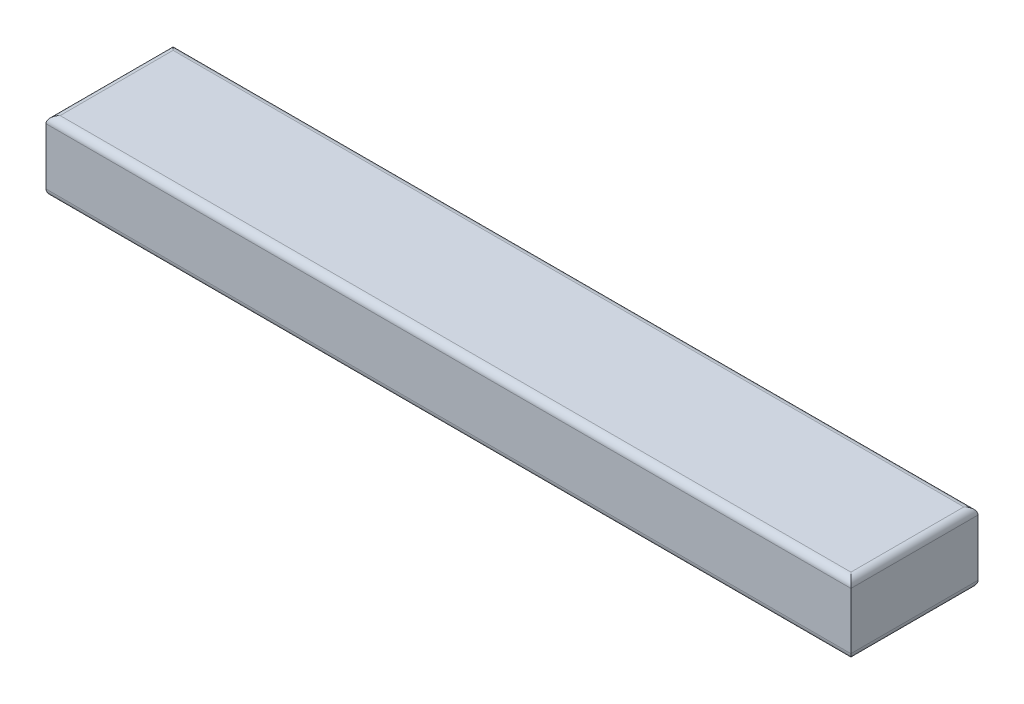
SolidWorks part; units mm, degrees
material "NEOPRENE"
ref_plane "Front Plane" through (0, 0, 0) normal (0, 0, 1) x (1, 0, 0)
ref_plane "Top Plane" through (0, 0, 0) normal (0, 1, 0) x (1, 0, 0)
ref_plane "Right Plane" through (0, 0, 0) normal (1, 0, 0) x (0, 0, -1)
sketch "Sketch2" plane through (0, 0, 0) normal (0, 1, 0) x (1, 0, 0)
  line L0 (0, 4.4849) -> (0, -5.3561) construction
  line L2 (-8.8619, 0) -> (9.144, 0) construction
  line L3 (14.478, -2.286) -> (-14.478, -2.286)
  line L4 (14.478, -2.286) -> (14.478, 2.286)
  line L5 (14.478, 2.286) -> (-14.478, 2.286)
  line L6 (-14.478, -2.286) -> (-14.478, 2.286)
  line L7 (14.478, -2.286) -> (-14.478, 2.286) construction
  line L8 (14.478, 2.286) -> (-14.478, -2.286) construction
  point P4 (0, 0)
  dimension "D1" = 4.572
  dimension "D2" = 28.956
extrude "Boss-Extrude1" add sketch "Sketch2" along normal blind 2.54
fillet "Fillet1" radius 0.254 8 edges at (0, 0, 2.286) (14.478, 0, 0) (0, 0, -2.286) (-14.478, 0, 0) (0, 2.54, -2.286) (14.478, 2.54, 0) (0, 2.54, 2.286) (-14.478, 2.54, 0)
